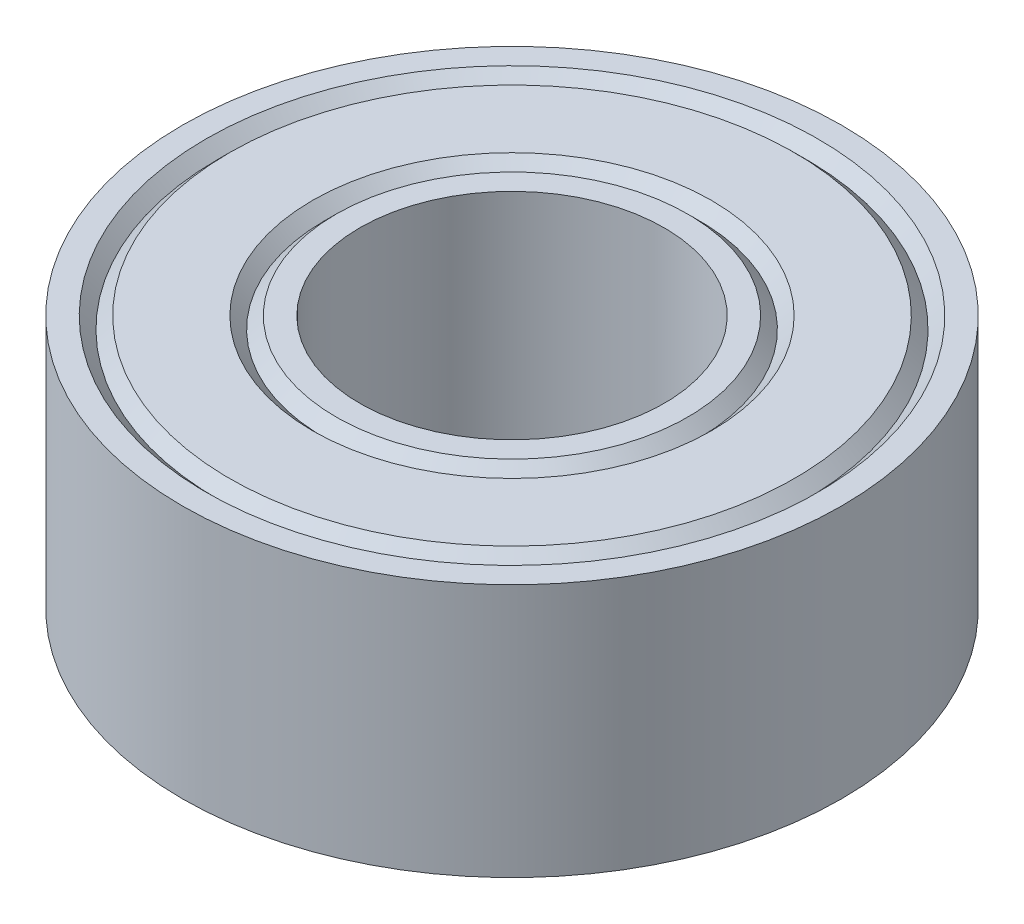
SolidWorks part; units mm, degrees
ref_plane "Front Plane" through (0, 0, 0) normal (0, 0, 1) x (1, 0, 0)
ref_plane "Top Plane" through (0, 0, 0) normal (0, 1, 0) x (1, 0, 0)
ref_plane "Right Plane" through (0, 0, 0) normal (1, 0, 0) x (0, 0, -1)
sketch "Sketch1" plane through (0, 0, 0) normal (0, 0, 1) x (1, 0, 0)
  line L0 (0, 2.5) -> (0, -2.5) construction
  line L1 (-3, 2.5) -> (-3.4667, 2.5)
  line L2 (-3, 2.5) -> (-3, -2.5)
  line L3 (-3, -2.5) -> (-3.4667, -2.5)
  line L4 (-6.5, 2.5) -> (-6.5, -2.5)
  line L5 (-6.0333, 2.5) -> (-5.8, 2.2667)
  line L6 (-5.8, 2.2667) -> (-5.5667, 2.5)
  line L7 (-3.9333, 2.5) -> (-3.7, 2.2667)
  line L8 (-3.7, 2.2667) -> (-3.4667, 2.5)
  line L9 (-6.0333, -2.5) -> (-5.8, -2.2667)
  line L10 (-5.8, -2.2667) -> (-5.5667, -2.5)
  line L11 (-3.9333, -2.5) -> (-3.7, -2.2667)
  line L12 (-3.7, -2.2667) -> (-3.4667, -2.5)
  line L13 (-3.9333, -2.5) -> (-5.5667, -2.5)
  line L14 (-6.0333, -2.5) -> (-6.5, -2.5)
  line L15 (-6.0333, 2.5) -> (-6.5, 2.5)
  line L16 (-3.9333, 2.5) -> (-5.5667, 2.5)
  line L17 (-5.8, 2.2667) -> (-3.7, 2.2667) construction
  line L18 (-5.8, 2.2667) -> (-5.8, -2.2667) construction
  line L19 (-3.7, -2.2667) -> (-5.8, -2.2667) construction
  line L20 (-3.7, 2.2667) -> (-3.7, -2.2667) construction
  line L21 (-5.8, 0) -> (-5.1, 0) construction
  line L22 (-3.4667, 2.5) -> (-3.9333, 2.5) construction
  line L23 (-5.1, 0) -> (-4.4, 0) construction
  line L24 (-5.8, 0) -> (-6.5, 0) construction
  line L25 (-4.4, 0) -> (-3.7, 0) construction
  line L26 (-3.7, 0) -> (-3, 0) construction
  dimension "D1" = 5
  dimension "D2" = 6
  dimension "D3" = 13
revolve "Revolve1" add sketch "Sketch1" angle 360 about L0
